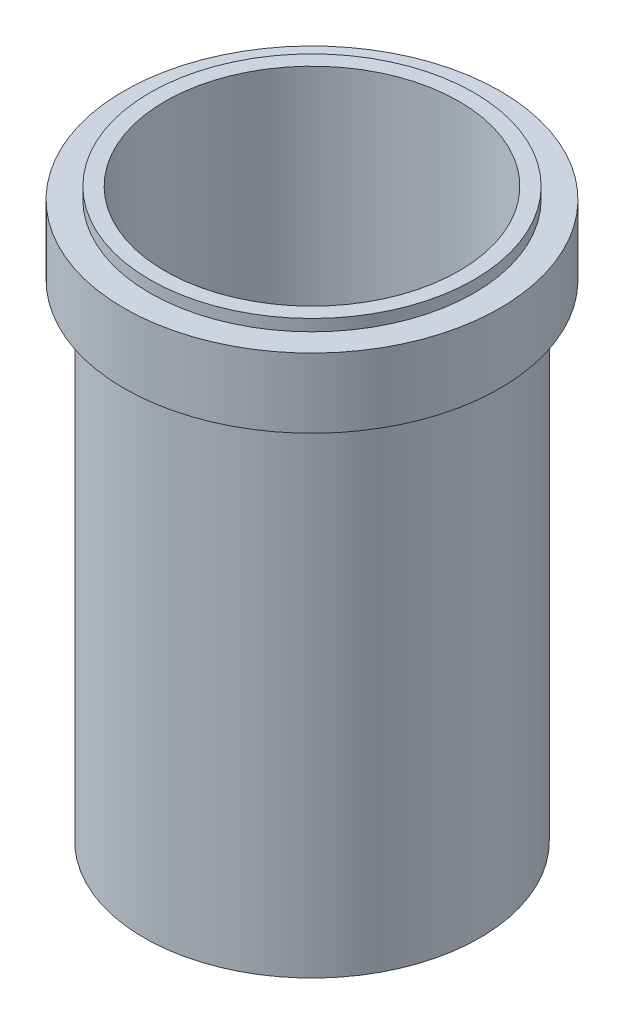
SolidWorks part; units mm, degrees
material "3.1305 (EN-AW 2117)"
ref_plane "Plan de face" through (0, 0, 0) normal (0, 0, 1) x (1, 0, 0)
ref_plane "Plan de dessus" through (0, 0, 0) normal (0, 1, 0) x (1, 0, 0)
ref_plane "Plan de droite" through (0, 0, 0) normal (1, 0, 0) x (0, 0, -1)
sketch "Esquisse1" plane through (0, 0, 0) normal (0, 0, 1) x (1, 0, 0)
  line L0 (0, 0) -> (0, 142.61) construction
  line L1 (25.4, 113.3062) -> (25.4, 15.3062)
  line L2 (25.4, 15.3062) -> (29, 15.3062)
  line L5 (29, 15.3062) -> (29, 99.3062)
  line L6 (29, 99.3062) -> (32.5, 99.3062)
  line L8 (28, 111.3062) -> (32.5, 111.3062)
  line L9 (32.5, 99.3062) -> (32.5, 111.3062)
  line L12 (25.4, 113.3062) -> (28, 113.3062)
  line L13 (28, 111.3062) -> (28, 113.3062)
  dimension "D1" = 28
  dimension "D2" = 50.8
  dimension "D3" = 32.5
  dimension "D4" = 84
  dimension "D5" = 2
  dimension "D6" = 12
  dimension "D7" = 32.5
  dimension "D8" = 29
revolve "Révolution1" add sketch "Esquisse1" angle 360 about L0
